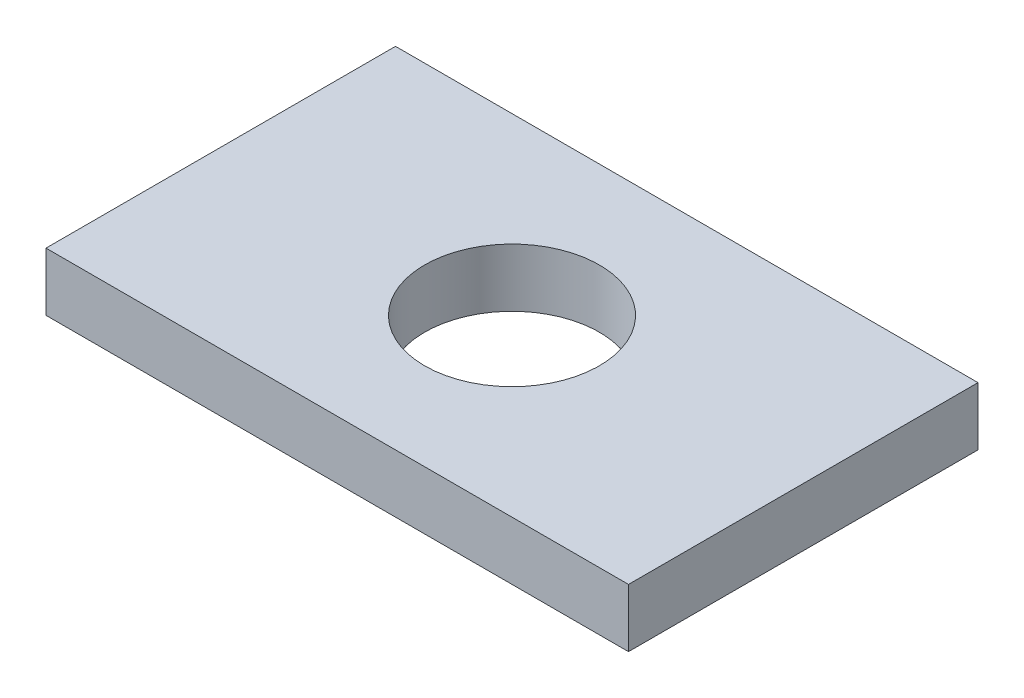
SolidWorks part; units mm, degrees
ref_plane "Front Plane" through (0, 0, 0) normal (0, 0, 1) x (1, 0, 0)
ref_plane "Top Plane" through (0, 0, 0) normal (0, 1, 0) x (1, 0, 0)
ref_plane "Right Plane" through (0, 0, 0) normal (1, 0, 0) x (0, 0, -1)
sketch "Sketch1" plane through (0, 0, 0) normal (0, 1, 0) x (1, 0, 0)
  line L1 (0, 0) -> (20, 0)
  line L2 (0, 0) -> (0, 12)
  line L3 (0, 12) -> (20, 12)
  line L4 (20, 0) -> (20, 12)
  circle A0 centre (10, 6) radius 3
  point P7 (0, 6)
  dimension "D3" = 6
  dimension "D1" = 12
  dimension "D2" = 20
  dimension "D4" = 0
extrude "Boss-Extrude1" add sketch "Sketch1" along normal blind 2
